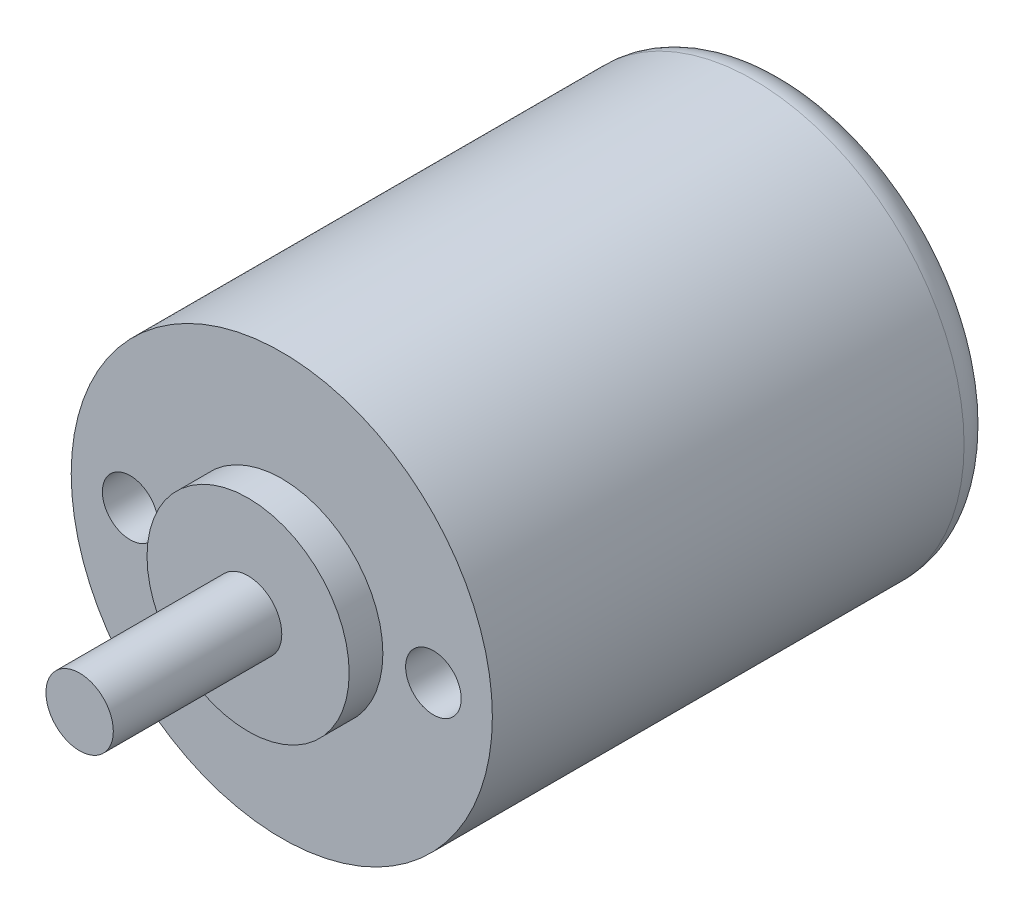
SolidWorks part; units mm, degrees
ref_plane "前视基准面" through (0, 0, 0) normal (0, 0, 1) x (1, 0, 0)
ref_plane "上视基准面" through (0, 0, 0) normal (0, 1, 0) x (1, 0, 0)
ref_plane "右视基准面" through (0, 0, 0) normal (1, 0, 0) x (0, 0, -1)
sketch "草图1" plane through (0, 0, 0) normal (0, 0, 1) x (1, 0, 0)
  circle A0 centre (0, 0) radius 12.5
extrude "凸台-拉伸1" add sketch "草图1" along normal blind 30
sketch "草图3" plane through (0, 0, 30) normal (0, 0, 1) x (1, 0, 0)
  circle A0 centre (0, 0) radius 9
  circle A1 centre (-9, 0) radius 1.65
  circle A2 centre (9, 0) radius 1.65
extrude "切除-拉伸1" cut sketch "草图3" against normal blind 4 contours A0 A1 | A0 A1 | A0 A2 | A0 A2
sketch "草图4" plane through (0, 0, 30) normal (0, 0, 1) x (1, 0, 0)
  circle A0 centre (0, 0) radius 6
extrude "凸台-拉伸2" add sketch "草图4" along normal blind 2
sketch "草图5" plane through (0, 0, 32) normal (0, 0, 1) x (1, 0, 0)
  circle A0 centre (0, 0) radius 2
extrude "凸台-拉伸3" add sketch "草图5" along normal blind 10
fillet "圆角1" radius 2 1 edges at (12.5, 0, 0)
